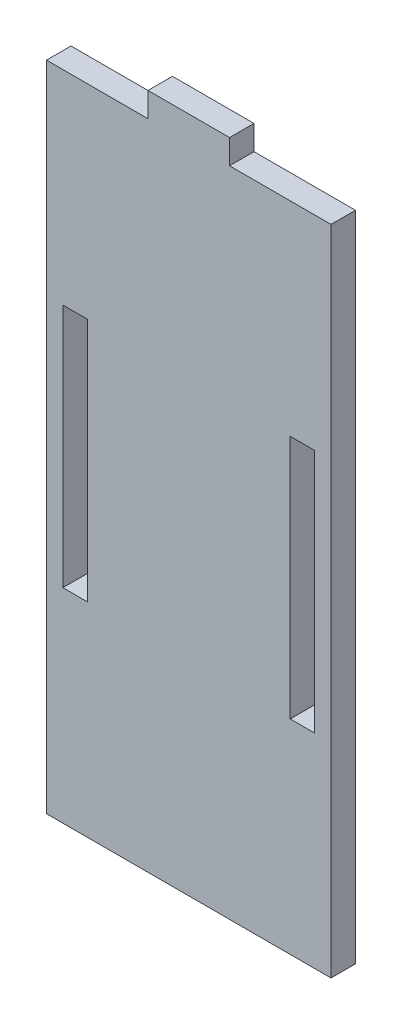
SolidWorks part; units mm, degrees
ref_plane "前视基准面" through (0, 0, 0) normal (0, 0, 1) x (1, 0, 0)
ref_plane "上视基准面" through (0, 0, 0) normal (0, 1, 0) x (1, 0, 0)
ref_plane "右视基准面" through (0, 0, 0) normal (1, 0, 0) x (0, 0, -1)
sketch "草图1" plane through (0, 0, 0) normal (0, 0, 1) x (1, 0, 0)
  line L0 (0, -40) -> (34.87, -40)
  line L1 (0, 0) -> (34.87, 0)
  line L2 (0, 0) -> (0, -80)
  line L3 (0, -80) -> (34.87, -80)
  line L4 (34.87, 0) -> (34.87, -80)
  line L5 (17.435, 0) -> (17.435, -80)
  line L6 (32.87, -55) -> (29.87, -55)
  line L11 (2, -25) -> (5, -25)
  line L12 (2, -25) -> (2, -55)
  line L13 (2, -55) -> (5, -55)
  line L14 (5, -25) -> (5, -55)
  line L15 (29.87, -25) -> (29.87, -55)
  line L16 (32.87, -25) -> (29.87, -25)
  line L17 (32.87, -25) -> (32.87, -55)
  line L19 (12.435, 0) -> (22.435, 0)
  line L20 (12.435, 0) -> (12.435, 3)
  line L21 (12.435, 3) -> (22.435, 3)
  line L22 (22.435, 0) -> (22.435, 3)
  dimension "D1" = 34.87
  dimension "D2" = 80
  dimension "D3" = 3
  dimension "D4" = 15
  dimension "D5" = 30
  dimension "D6" = 2
  dimension "D7" = 10
  dimension "D8" = 3
  dimension "D9" = 5
extrude "凸台-拉伸1" add sketch "草图1" along normal blind 3 contours L11 L14 L0 L5 L1 L2 L12 | L0 L14 L13 L12 L2 L3 L5 | L0 L17 L6 L15 L5 L3 L4 | L16 L17 L0 L4 L1 L5 L15 | L1 L22 L21 L20
